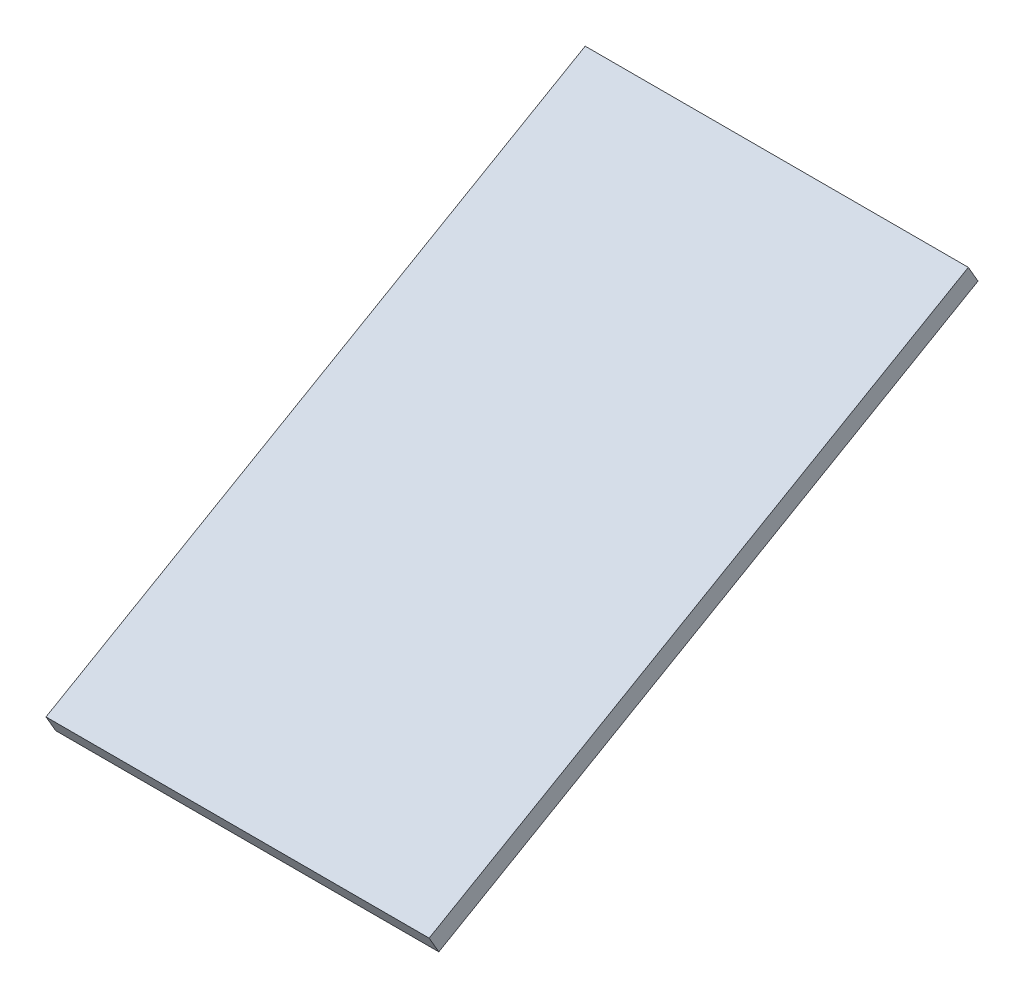
SolidWorks part; units mm, degrees
ref_plane "Front Plane" through (0, 0, 0) normal (0, 0, 1) x (1, 0, 0)
ref_plane "Top Plane" through (0, 0, 0) normal (0, 1, 0) x (1, 0, 0)
ref_plane "Right Plane" through (0, 0, 0) normal (1, 0, 0) x (0, 0, -1)
sketch "Sketch1" plane through (0, 0, 0) normal (1, 0, 0) x (0, 0, -1)
  line L0 (0, 0) -> (1429.8079, 825.5) construction
  line L1 (1429.8079, 825.5) -> (1429.8079, 0) construction
  line L2 (1429.8079, 0) -> (0, 0) construction
  line L3 (0, 0) -> (1429.8079, 825.5)
  line L4 (0, 0) -> (-25.6504, 44.4277)
  line L5 (1429.8079, 825.5) -> (1404.1576, 869.9277)
  line L6 (-25.6504, 44.4277) -> (1404.1576, 869.9277)
  dimension "D1" = 30
  dimension "D2" = 1651
extrude "Boss-Extrude1" add sketch "Sketch1" along normal blind 1016
